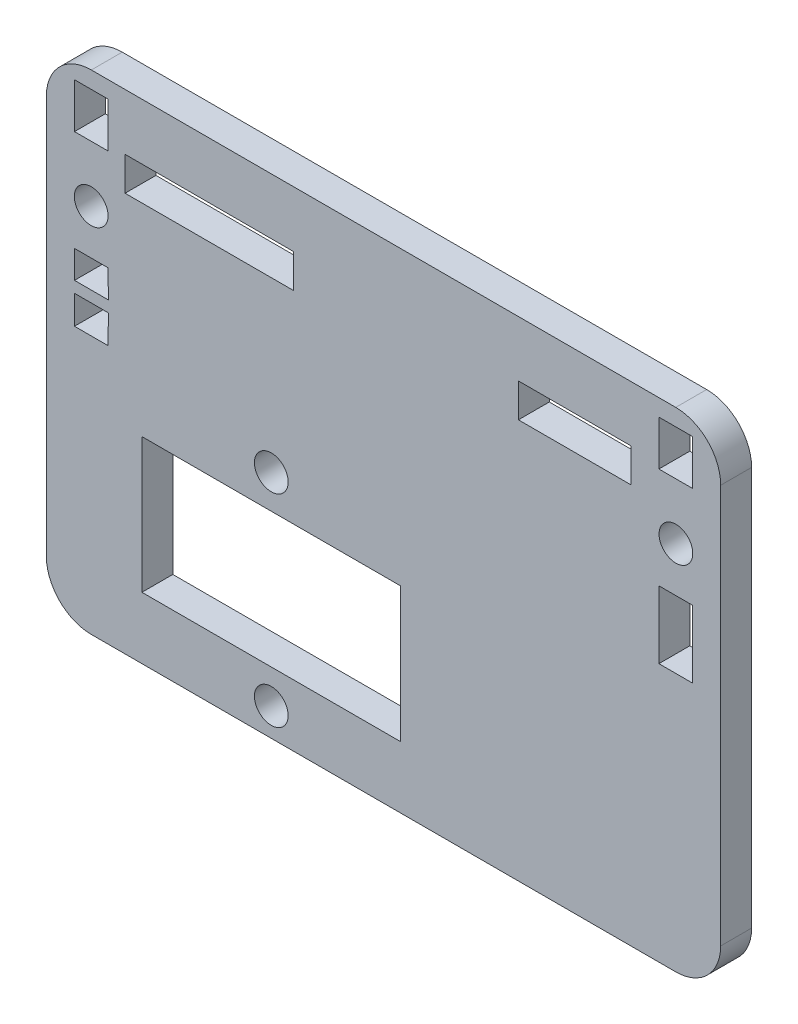
SolidWorks part; units mm, degrees
ref_plane "Ön Düzlem" through (0, 0, 0) normal (0, 0, 1) x (1, 0, 0)
ref_plane "Üst Düzlem" through (0, 0, 0) normal (0, 1, 0) x (1, 0, 0)
ref_plane "Sağ Düzlem" through (0, 0, 0) normal (1, 0, 0) x (0, 0, -1)
sketch "Sketch1" plane through (0, 0, 0) normal (0, 0, 1) x (1, 0, 0)
  line L1 (-37.3824, -24.8481) -> (22.6176, -24.8481)
  line L2 (-37.3824, -24.8481) -> (-37.3824, 18.6519)
  line L3 (-37.3824, 18.6519) -> (22.6176, 18.6519)
  line L4 (22.6176, -24.8481) -> (22.6176, 18.6519)
  line L5 (-28.8824, -19.3481) -> (-5.8824, -19.3481)
  line L6 (-28.8824, -19.3481) -> (-28.8824, -7.3481)
  line L7 (-28.8824, -7.3481) -> (-5.8824, -7.3481)
  line L8 (-5.8824, -19.3481) -> (-5.8824, -7.3481)
  line L9 (-28.8824, -19.3481) -> (-5.8824, -7.3481) construction
  line L10 (-28.8824, -7.3481) -> (-5.8824, -19.3481) construction
  line L11 (-30.3824, 13.6519) -> (-15.3824, 13.6519)
  line L12 (-30.3824, 13.6519) -> (-30.3824, 10.6519)
  line L13 (-30.3824, 10.6519) -> (-15.3824, 10.6519)
  line L14 (-15.3824, 13.6519) -> (-15.3824, 10.6519)
  line L15 (4.6176, 13.6913) -> (14.6176, 13.6913)
  line L16 (4.6176, 13.6913) -> (4.6176, 10.6913)
  line L17 (4.6176, 10.6913) -> (14.6176, 10.6913)
  line L18 (14.6176, 13.6913) -> (14.6176, 10.6913)
  line L19 (17.1176, -1.8481) -> (20.1176, -1.8481)
  line L20 (17.1176, -1.8481) -> (17.1176, 4.1519)
  line L21 (17.1176, 4.1519) -> (20.1176, 4.1519)
  line L22 (20.1176, -1.8481) -> (20.1176, 4.1519)
  line L23 (20.1176, 17.1519) -> (17.1176, 17.1519)
  line L24 (20.1176, 17.1519) -> (20.1176, 13.1519)
  line L25 (20.1176, 13.1519) -> (17.1176, 13.1519)
  line L26 (17.1176, 17.1519) -> (17.1176, 13.1519)
  line L27 (-31.8824, 4.1519) -> (-34.8824, 4.1519)
  line L28 (-34.8824, -1.8481) -> (-34.8824, 0.6937)
  line L29 (-31.8824, -1.8481) -> (-34.8824, -1.8481)
  line L31 (-34.8824, 13.1519) -> (-31.8824, 13.1519)
  line L32 (-31.8824, 17.1519) -> (-31.8824, 13.1519)
  line L33 (-34.8824, 17.1519) -> (-31.8824, 17.1519)
  line L34 (-34.8824, 17.1519) -> (-34.8824, 13.1519)
  line L40 (-34.8824, 1.6889) -> (-34.8824, 4.1519)
  line L41 (-31.8824, 4.1519) -> (-31.8746, 1.6889)
  line L42 (-34.8824, 1.6889) -> (-31.8746, 1.6889)
  line L43 (-31.8746, 0.6937) -> (-31.8824, -1.8481)
  line L45 (-34.8824, 0.6937) -> (-31.8746, 0.6937)
  circle A0 centre (-17.3693, -22.3481) radius 1.5
  circle A1 centre (-17.3693, -4.3481) radius 1.5
  circle A2 centre (18.6307, 8.1519) radius 1.5
  circle A3 centre (-33.3955, 8.1519) radius 1.5
  point P0 (0, 0)
  point P6 (-17.3824, -13.3481)
  dimension "D7" = 3
  dimension "D9" = 3
  dimension "D1" = 60
  dimension "D2" = 43.5
  dimension "D3" = 23
  dimension "D4" = 12
  dimension "D5" = 5.5
  dimension "D6" = 8.5
  dimension "D8" = 3
  dimension "D10" = 3
  dimension "D11" = 3
  dimension "D12" = 15
  dimension "D13" = 5
  dimension "D14" = 7
  dimension "D15" = 20
  dimension "D16" = 10
  dimension "D17" = 2.5
  dimension "D18" = 3
  dimension "D19" = 6
  dimension "D20" = 23
  dimension "D21" = 10
  dimension "D22" = 4
  dimension "D23" = 3
  dimension "D24" = 2.5
  dimension "D25" = 1.5
extrude "Boss-Extrude1" add sketch "Sketch1" along normal blind 2.75
fillet "Fillet1" radius 4 4 edges at (22.6176, -24.8481, 1.375) (-37.3824, -24.8481, 1.375) (-37.3824, 18.6519, 1.375) (22.6176, 18.6519, 1.375)
